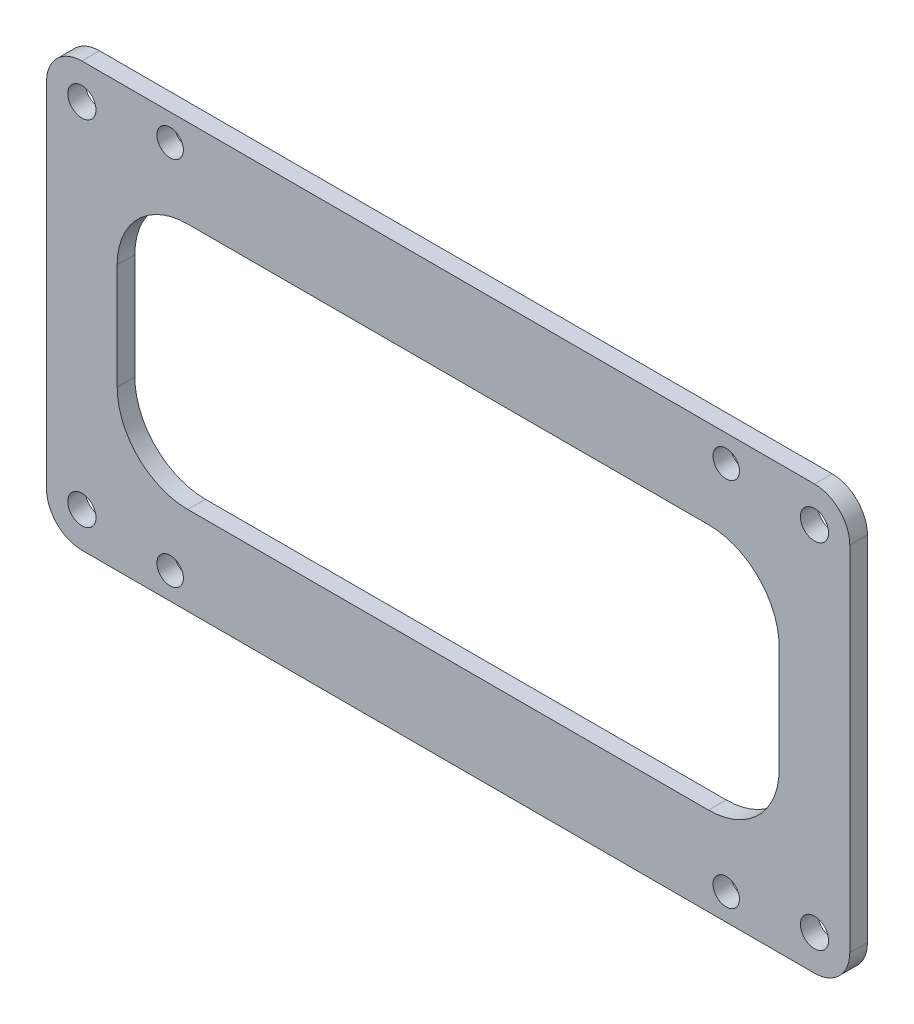
SolidWorks part; units mm, degrees
material "Thornel Mat VMA"
ref_plane "前视基准面" through (0, 0, 0) normal (0, 0, 1) x (1, 0, 0)
ref_plane "上视基准面" through (0, 0, 0) normal (0, 1, 0) x (1, 0, 0)
ref_plane "右视基准面" through (0, 0, 0) normal (1, 0, 0) x (0, 0, -1)
sketch "草图1" plane through (0, 0, 0) normal (0, 0, 1) x (1, 0, 0)
  line L1 (31.5, -21) -> (-31.5, -21) construction
  line L2 (31.5, -21) -> (31.5, 21) construction
  line L3 (31.5, 21) -> (-31.5, 21) construction
  line L4 (-31.5, -21) -> (-31.5, 21) construction
  line L5 (31.5, -21) -> (-31.5, 21) construction
  line L6 (31.5, 21) -> (-31.5, -21) construction
  line L7 (41.5, -24) -> (-41.5, -24)
  line L8 (45.5, -20) -> (45.5, 20)
  line L9 (41.5, 24) -> (-41.5, 24)
  line L10 (-45.5, -20) -> (-45.5, 20)
  line L11 (45.5, -24) -> (-45.5, 24) construction
  line L12 (45.5, 24) -> (-45.5, -24) construction
  line L13 (41.5, -20) -> (-41.5, -20) construction
  line L14 (41.5, -20) -> (41.5, 20) construction
  line L15 (41.5, 20) -> (-41.5, 20) construction
  line L16 (-41.5, -20) -> (-41.5, 20) construction
  line L17 (41.5, -20) -> (-41.5, 20) construction
  line L18 (41.5, 20) -> (-41.5, -20) construction
  line L19 (29.5, -14) -> (-29.5, -14)
  line L20 (37.5, -6) -> (37.5, 6)
  line L21 (29.5, 14) -> (-29.5, 14)
  line L22 (-37.5, -6) -> (-37.5, 6)
  line L23 (37.5, -14) -> (-37.5, 14) construction
  line L24 (37.5, 14) -> (-37.5, -14) construction
  circle A0 centre (-31.5, 21) radius 1.5
  circle A1 centre (31.5, 21) radius 1.5
  circle A2 centre (31.5, -21) radius 1.5
  circle A3 centre (-31.5, -21) radius 1.5
  circle A4 centre (-41.5, 20) radius 1.6
  circle A5 centre (-41.5, -20) radius 1.6
  circle A6 centre (41.5, 20) radius 1.6
  circle A7 centre (41.5, -20) radius 1.6
  arc A8 (-41.5, -24) -> (-45.5, -20) centre (-41.5, -20) cw
  arc A9 (45.5, 20) -> (41.5, 24) centre (41.5, 20) ccw
  arc A10 (41.5, -24) -> (45.5, -20) centre (41.5, -20) ccw
  arc A11 (-41.5, 24) -> (-45.5, 20) centre (-41.5, 20) ccw
  arc A12 (-29.5, -14) -> (-37.5, -6) centre (-29.5, -6) cw
  arc A13 (37.5, 6) -> (29.5, 14) centre (29.5, 6) ccw
  arc A14 (29.5, -14) -> (37.5, -6) centre (29.5, -6) ccw
  arc A15 (-29.5, 14) -> (-37.5, 6) centre (-29.5, 6) ccw
  point P0 (0, 0)
  point P10 (0, 0)
  point P15 (0, 0)
  point P36 (0, 0)
  dimension "D3" = 3
  dimension "D6" = 3.2
  dimension "D7" = 4
  dimension "D10" = 8
  dimension "D1" = 63
  dimension "D2" = 42
  dimension "D4" = 83
  dimension "D5" = 40
  dimension "D8" = 8
  dimension "D9" = 10
extrude "凸台-拉伸1" add sketch "草图1" along normal blind 2
